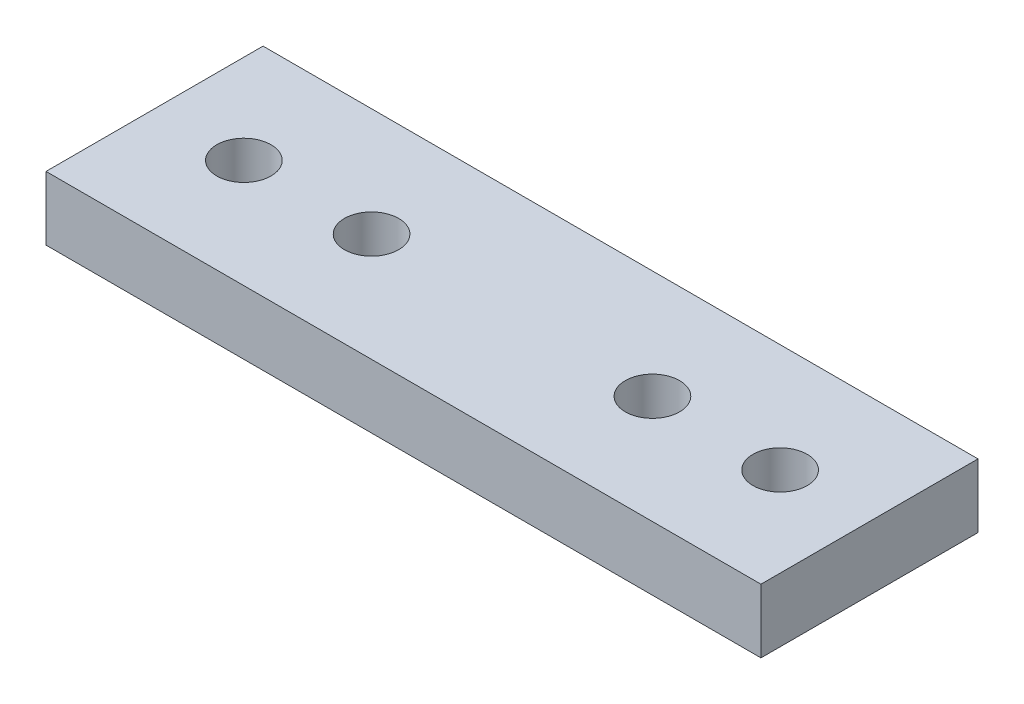
SolidWorks part; units mm, degrees
ref_plane "Front Plane" through (0, 0, 0) normal (0, 0, 1) x (1, 0, 0)
ref_plane "Top Plane" through (0, 0, 0) normal (0, 1, 0) x (1, 0, 0)
ref_plane "Right Plane" through (0, 0, 0) normal (1, 0, 0) x (0, 0, -1)
sketch "Sketch1" plane through (0, 0, 0) normal (0, 1, 0) x (1, 0, 0)
  line L1 (-56, -17) -> (56, -17)
  line L2 (-56, -17) -> (-56, 17)
  line L3 (-56, 17) -> (56, 17)
  line L4 (56, -17) -> (56, 17)
  circle A0 centre (-42, 0) radius 4.25
  circle A1 centre (42, 0) radius 4.25
  circle A2 centre (-22, 0) radius 4.25
  circle A3 centre (22, 0) radius 4.25
extrude "Plate_Extrude" add sketch "Sketch1" along normal blind 10
equation "\"ValveDiameter\" = 50mm"
equation "\"MotorGearTeeth\" = 40"
equation "\"OutputGearTeeth\" = 80"
equation "\"GearModule\" = 1.5mm"
equation "\"PressureAngle\" = 20deg"
equation "\"GearCenterDistance\" = 90mm"
equation "\"GearWidth\" = 18mm"
equation "\"OutputShaftDiameter\" = 20mm"
equation "\"BearingOD\" = 47mm"
equation "\"BearingWidth\" = 14mm"
equation "\"PlateThickness\" = 6mm"
equation "\"ValveRotation\" = 90deg"
